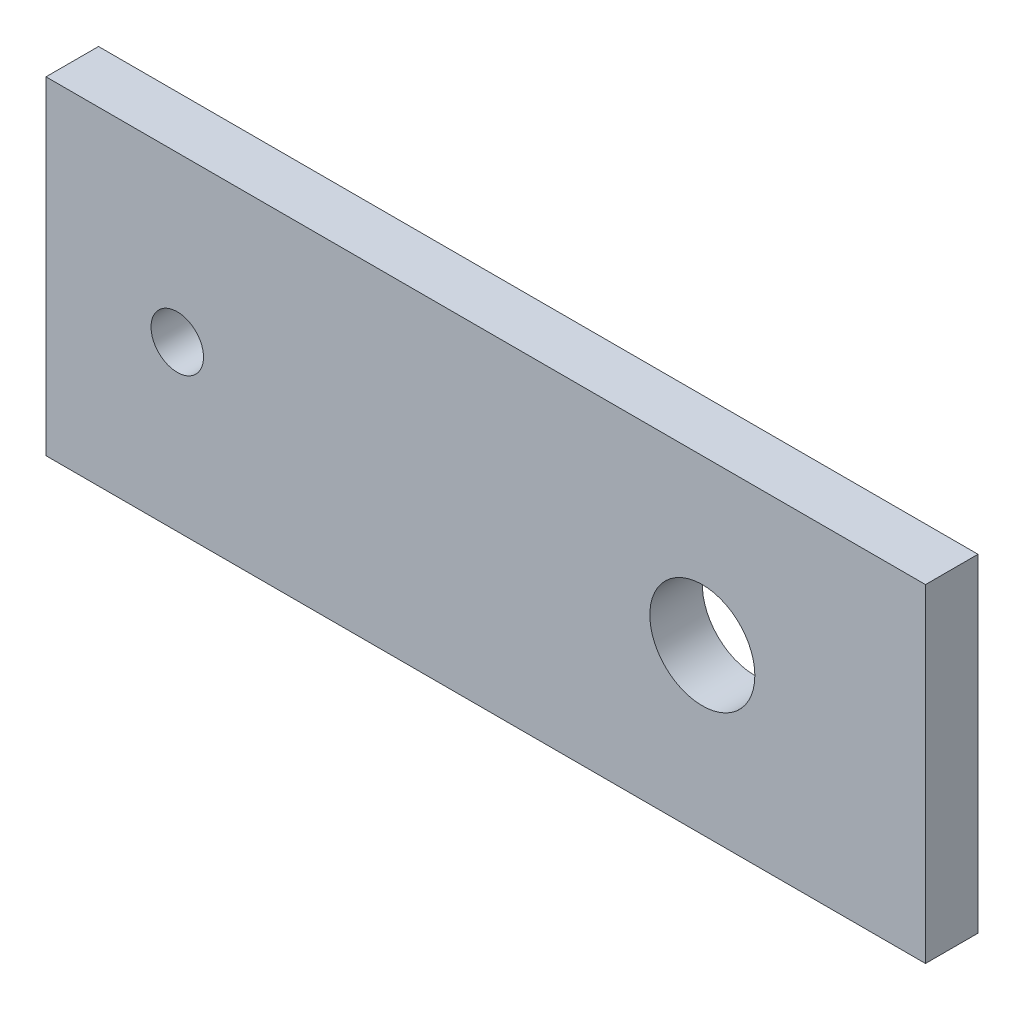
SolidWorks part; units mm, degrees
ref_plane "前视基准面" through (0, 0, 0) normal (0, 0, 1) x (1, 0, 0)
ref_plane "上视基准面" through (0, 0, 0) normal (0, 1, 0) x (1, 0, 0)
ref_plane "右视基准面" through (0, 0, 0) normal (1, 0, 0) x (0, 0, -1)
sketch "草图1" plane through (0, 0, 0) normal (0, 0, 1) x (1, 0, 0)
  line L1 (-44.8441, 30.4566) -> (22.1559, 30.4566)
  line L2 (-44.8441, 30.4566) -> (-44.8441, 5.4566)
  line L3 (-44.8441, 5.4566) -> (22.1559, 5.4566)
  line L4 (22.1559, 30.4566) -> (22.1559, 5.4566)
  dimension "D1" = 67
  dimension "D2" = 25
extrude "凸台-拉伸1" add sketch "草图1" along normal blind 4
sketch "草图2" plane through (0, 0, 4) normal (0, 0, 1) x (1, 0, 0)
  circle A0 centre (-34.8441, 17.9566) radius 2
  circle A1 centre (5.1559, 17.9566) radius 4
  dimension "D3" = 8
  dimension "D4" = 4
  dimension "D2" = 40
extrude "切除-拉伸1" cut sketch "草图2" against normal blind 4
